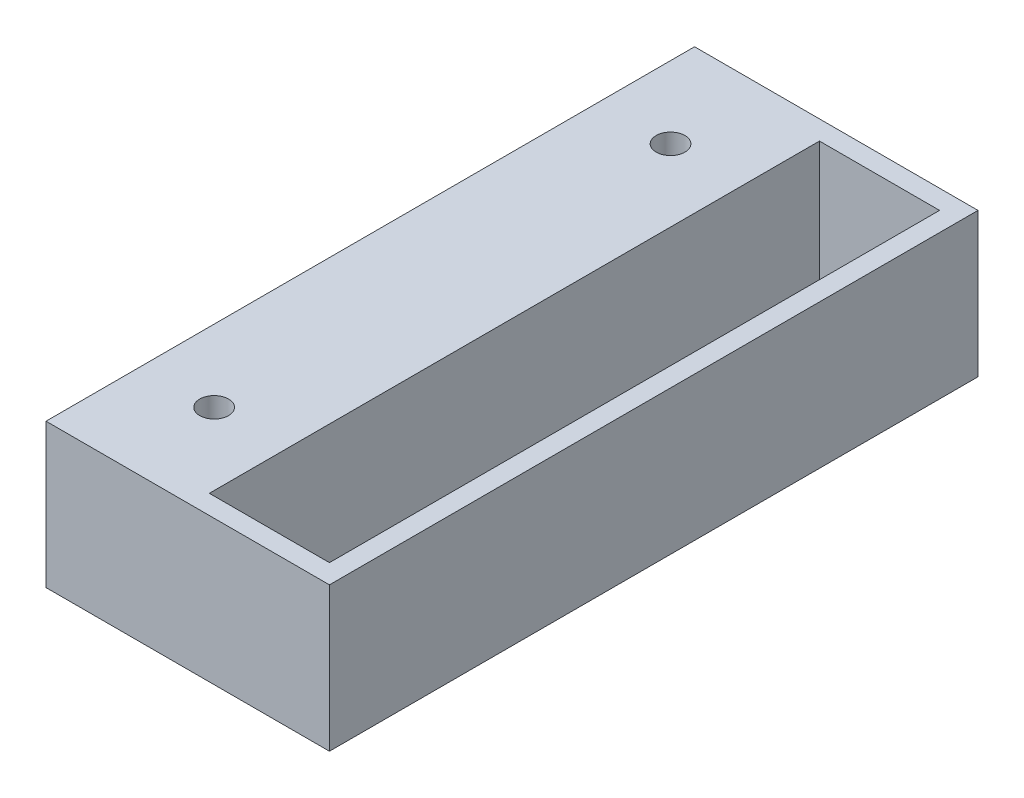
SolidWorks part; units mm, degrees
ref_plane "Alzado" through (0, 0, 0) normal (0, 0, 1) x (1, 0, 0)
ref_plane "Planta" through (0, 0, 0) normal (0, 1, 0) x (1, 0, 0)
ref_plane "Vista lateral" through (0, 0, 0) normal (1, 0, 0) x (0, 0, -1)
sketch "Croquis1" plane through (0, 0, 0) normal (0, 1, 0) x (1, 0, 0)
  line L0 (-8.25, 33.75) -> (8.25, 33.75)
  line L1 (-6.25, -31.75) -> (6.25, -31.75)
  line L2 (-6.25, -31.75) -> (-6.25, 31.75)
  line L3 (-6.25, 31.75) -> (6.25, 31.75)
  line L4 (6.25, -31.75) -> (6.25, 31.75)
  line L5 (-6.25, -31.75) -> (6.25, 31.75) construction
  line L6 (-6.25, 31.75) -> (6.25, -31.75) construction
  line L7 (8.25, -33.75) -> (8.25, 33.75)
  line L8 (-8.25, -33.75) -> (8.25, -33.75)
  line L9 (-6.25, 31.75) -> (-21.25, 31.75) construction
  line L10 (-8.25, -33.75) -> (-21.25, -33.75)
  line L11 (-21.25, -33.75) -> (-21.25, 33.75)
  line L12 (-8.25, 33.75) -> (-21.25, 33.75)
  line L13 (-21.25, 31.75) -> (-13.75, 31.75) construction
  line L14 (-8.25, -33.75) -> (-8.25, 33.75) construction
  line L15 (-13.75, 31.75) -> (-13.75, -30.4031) construction
  circle A0 centre (-13.75, -23.75) radius 1.5
  circle A1 centre (-13.75, 23.75) radius 1.5
  point P0 (0, 0)
  dimension "D5" = 10
  dimension "D7" = 3
  dimension "D8" = 3
  dimension "D1" = 63.5
  dimension "D2" = 12.5
  dimension "D4" = 29.5
  dimension "D6" = 10
  dimension "D3" = 2
extrude "Saliente-Extruir1" add sketch "Croquis1" along normal blind 15
